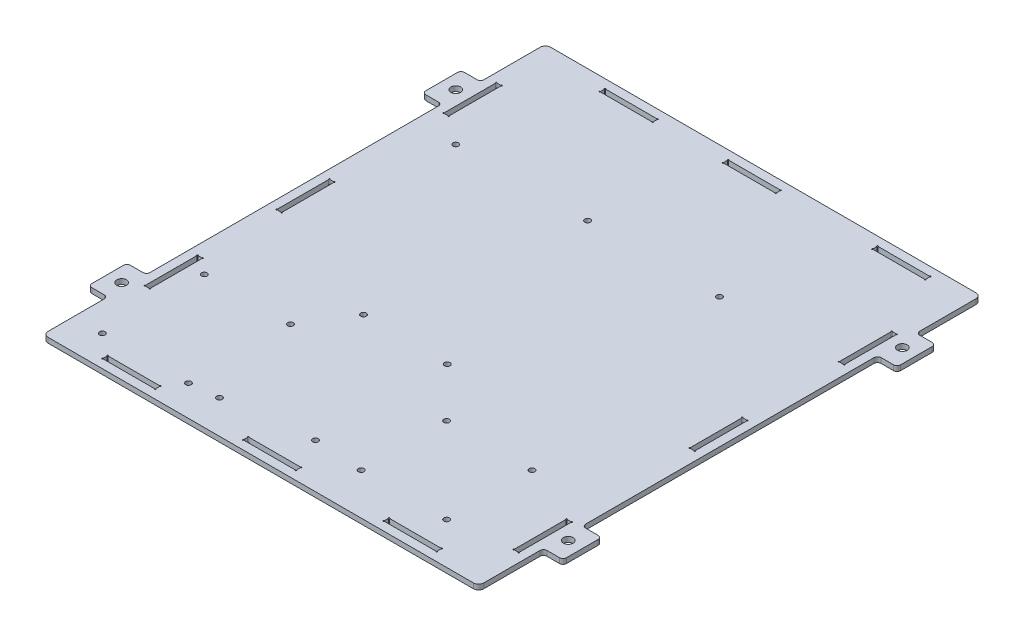
SolidWorks part; units mm, degrees
material "Acrylic (Medium-high impact)"
ref_plane "Front Plane" through (0, 0, 0) normal (0, 0, 1) x (1, 0, 0)
ref_plane "Top Plane" through (0, 0, 0) normal (0, 1, 0) x (1, 0, 0)
ref_plane "Right Plane" through (0, 0, 0) normal (1, 0, 0) x (0, 0, -1)
sketch "Sketch1" plane through (0, 0, 0) normal (0, 1, 0) x (1, 0, 0)
  line L0 (-120.9, -142.9) -> (120.9, -142.9)
  line L1 (123.9, -139.9) -> (123.9, -108)
  line L2 (125.9, -106) -> (133, -106)
  line L3 (135, -104) -> (135, -86)
  line L4 (133, -84) -> (125.9, -84)
  line L5 (123.9, -82) -> (123.9, 82)
  line L6 (125.9, 84) -> (133, 84)
  line L7 (135, 86) -> (135, 104)
  line L8 (133, 106) -> (125.9, 106)
  line L9 (123.9, 108) -> (123.9, 139.9)
  line L10 (120.9, 142.9) -> (-120.9, 142.9)
  line L11 (-123.9, 139.9) -> (-123.9, 108)
  line L12 (-125.9, 106) -> (-133, 106)
  line L13 (-135, 104) -> (-135, 86)
  line L14 (-133, 84) -> (-125.9, 84)
  line L15 (-123.9, 82) -> (-123.9, -82)
  line L16 (-125.9, -84) -> (-133, -84)
  line L17 (-135, -86) -> (-135, -104)
  line L18 (-133, -106) -> (-125.9, -106)
  line L19 (-123.9, -108) -> (-123.9, -139.9)
  line L20 (-94.6375, -137.9) -> (-65.3625, -137.9)
  line L21 (-65.0125, -137.55) -> (-65.0125, -135.35)
  line L22 (-65.3625, -135) -> (-94.6375, -135)
  line L23 (-94.9875, -135.35) -> (-94.9875, -137.55)
  line L24 (-14.6375, -137.9) -> (14.6375, -137.9)
  line L25 (14.9875, -137.55) -> (14.9875, -135.35)
  line L26 (14.6375, -135) -> (-14.6375, -135)
  line L27 (-14.9875, -135.35) -> (-14.9875, -137.55)
  line L28 (65.3625, -137.9) -> (94.6375, -137.9)
  line L29 (94.9875, -137.55) -> (94.9875, -135.35)
  line L30 (94.6375, -135) -> (65.3625, -135)
  line L31 (65.0125, -135.35) -> (65.0125, -137.55)
  line L32 (-84.6375, 135) -> (-55.3625, 135)
  line L33 (-55.0125, 135.35) -> (-55.0125, 137.55)
  line L34 (-55.3625, 137.9) -> (-84.6375, 137.9)
  line L35 (-84.9875, 137.55) -> (-84.9875, 135.35)
  line L36 (-14.6375, 135) -> (14.6375, 135)
  line L37 (14.9875, 135.35) -> (14.9875, 137.55)
  line L38 (14.6375, 137.9) -> (-14.6375, 137.9)
  line L39 (-14.9875, 137.55) -> (-14.9875, 135.35)
  line L40 (70.3625, 135) -> (99.6375, 135)
  line L41 (99.9875, 135.35) -> (99.9875, 137.55)
  line L42 (99.6375, 137.9) -> (70.3625, 137.9)
  line L43 (70.0125, 137.55) -> (70.0125, 135.35)
  line L44 (116.35, -114.9875) -> (118.55, -114.9875)
  line L45 (118.9, -114.6375) -> (118.9, -85.3625)
  line L46 (118.55, -85.0125) -> (116.35, -85.0125)
  line L47 (116, -85.3625) -> (116, -114.6375)
  line L48 (116.35, -14.9875) -> (118.55, -14.9875)
  line L49 (118.9, -14.6375) -> (118.9, 14.6375)
  line L50 (118.55, 14.9875) -> (116.35, 14.9875)
  line L51 (116, 14.6375) -> (116, -14.6375)
  line L52 (116.35, 70.0125) -> (118.55, 70.0125)
  line L53 (118.9, 70.3625) -> (118.9, 99.6375)
  line L54 (118.55, 99.9875) -> (116.35, 99.9875)
  line L55 (116, 99.6375) -> (116, 70.3625)
  line L56 (-118.55, -89.9875) -> (-116.35, -89.9875)
  line L57 (-116, -89.6375) -> (-116, -60.3625)
  line L58 (-116.35, -60.0125) -> (-118.55, -60.0125)
  line L59 (-118.9, -60.3625) -> (-118.9, -89.6375)
  line L60 (-118.55, -14.9875) -> (-116.35, -14.9875)
  line L61 (-116, -14.6375) -> (-116, 14.6375)
  line L62 (-116.35, 14.9875) -> (-118.55, 14.9875)
  line L63 (-118.9, 14.6375) -> (-118.9, -14.6375)
  line L64 (-118.55, 80.0125) -> (-116.35, 80.0125)
  line L65 (-116, 80.3625) -> (-116, 109.6375)
  line L66 (-116.35, 109.9875) -> (-118.55, 109.9875)
  line L67 (-118.9, 109.6375) -> (-118.9, 80.3625)
  arc A0 (-123.9, -139.9) -> (-120.9, -142.9) centre (-120.9, -139.9) ccw
  arc A1 (120.9, -142.9) -> (123.9, -139.9) centre (120.9, -139.9) ccw
  arc A2 (125.9, -106) -> (123.9, -108) centre (125.9, -108) ccw
  arc A3 (133, -106) -> (135, -104) centre (133, -104) ccw
  arc A4 (135, -86) -> (133, -84) centre (133, -86) ccw
  arc A5 (123.9, -82) -> (125.9, -84) centre (125.9, -82) ccw
  arc A6 (125.9, 84) -> (123.9, 82) centre (125.9, 82) ccw
  arc A7 (133, 84) -> (135, 86) centre (133, 86) ccw
  arc A8 (135, 104) -> (133, 106) centre (133, 104) ccw
  arc A9 (123.9, 108) -> (125.9, 106) centre (125.9, 108) ccw
  arc A10 (123.9, 139.9) -> (120.9, 142.9) centre (120.9, 139.9) ccw
  arc A11 (-120.9, 142.9) -> (-123.9, 139.9) centre (-120.9, 139.9) ccw
  arc A12 (-125.9, 106) -> (-123.9, 108) centre (-125.9, 108) ccw
  arc A13 (-133, 106) -> (-135, 104) centre (-133, 104) ccw
  arc A14 (-135, 86) -> (-133, 84) centre (-133, 86) ccw
  arc A15 (-123.9, 82) -> (-125.9, 84) centre (-125.9, 82) ccw
  arc A16 (-125.9, -84) -> (-123.9, -82) centre (-125.9, -82) ccw
  arc A17 (-133, -84) -> (-135, -86) centre (-133, -86) ccw
  arc A18 (-135, -104) -> (-133, -106) centre (-133, -104) ccw
  arc A19 (-123.9, -108) -> (-125.9, -106) centre (-125.9, -108) ccw
  circle A20 centre (-107.5, -125.5) radius 1.6
  circle A21 centre (-107.5, -67.5) radius 1.6
  circle A22 centre (-58.5, -125.5) radius 1.6
  circle A23 centre (-58.5, -67.5) radius 1.6
  circle A24 centre (5.8, -42.64) radius 1.6
  circle A25 centre (5.8, -117.57) radius 1.6
  circle A26 centre (-42.46, -123.92) radius 1.6
  circle A27 centre (-42.46, -42) radius 1.6
  circle A28 centre (82.1, -70.7) radius 1.6
  circle A29 centre (82.1, -119.3) radius 1.6
  circle A30 centre (33.5, -70.7) radius 1.6
  circle A31 centre (33.5, -119.3) radius 1.6
  circle A32 centre (-100, 68) radius 1.6
  circle A33 centre (-25, 68) radius 1.6
  circle A34 centre (50, 68) radius 1.6
  circle A35 centre (-127, -95) radius 2.75
  circle A36 centre (-127, 95) radius 2.75
  circle A37 centre (127, -95) radius 2.75
  circle A38 centre (127, 95) radius 2.75
  arc A39 (-65.3625, -137.9) -> (-65.0125, -137.55) centre (-65.0125, -137.9) ccw
  arc A40 (-65.0125, -135.35) -> (-65.3625, -135) centre (-65.0125, -135) ccw
  arc A41 (-94.6375, -135) -> (-94.9875, -135.35) centre (-94.9875, -135) ccw
  arc A42 (-94.9875, -137.55) -> (-94.6375, -137.9) centre (-94.9875, -137.9) ccw
  arc A43 (14.6375, -137.9) -> (14.9875, -137.55) centre (14.9875, -137.9) ccw
  arc A44 (14.9875, -135.35) -> (14.6375, -135) centre (14.9875, -135) ccw
  arc A45 (-14.6375, -135) -> (-14.9875, -135.35) centre (-14.9875, -135) ccw
  arc A46 (-14.9875, -137.55) -> (-14.6375, -137.9) centre (-14.9875, -137.9) ccw
  arc A47 (94.6375, -137.9) -> (94.9875, -137.55) centre (94.9875, -137.9) ccw
  arc A48 (94.9875, -135.35) -> (94.6375, -135) centre (94.9875, -135) ccw
  arc A49 (65.3625, -135) -> (65.0125, -135.35) centre (65.0125, -135) ccw
  arc A50 (65.0125, -137.55) -> (65.3625, -137.9) centre (65.0125, -137.9) ccw
  arc A51 (-55.3625, 135) -> (-55.0125, 135.35) centre (-55.0125, 135) ccw
  arc A52 (-55.0125, 137.55) -> (-55.3625, 137.9) centre (-55.0125, 137.9) ccw
  arc A53 (-84.6375, 137.9) -> (-84.9875, 137.55) centre (-84.9875, 137.9) ccw
  arc A54 (-84.9875, 135.35) -> (-84.6375, 135) centre (-84.9875, 135) ccw
  arc A55 (14.6375, 135) -> (14.9875, 135.35) centre (14.9875, 135) ccw
  arc A56 (14.9875, 137.55) -> (14.6375, 137.9) centre (14.9875, 137.9) ccw
  arc A57 (-14.6375, 137.9) -> (-14.9875, 137.55) centre (-14.9875, 137.9) ccw
  arc A58 (-14.9875, 135.35) -> (-14.6375, 135) centre (-14.9875, 135) ccw
  arc A59 (99.6375, 135) -> (99.9875, 135.35) centre (99.9875, 135) ccw
  arc A60 (99.9875, 137.55) -> (99.6375, 137.9) centre (99.9875, 137.9) ccw
  arc A61 (70.3625, 137.9) -> (70.0125, 137.55) centre (70.0125, 137.9) ccw
  arc A62 (70.0125, 135.35) -> (70.3625, 135) centre (70.0125, 135) ccw
  arc A63 (118.55, -114.9875) -> (118.9, -114.6375) centre (118.9, -114.9875) ccw
  arc A64 (118.9, -85.3625) -> (118.55, -85.0125) centre (118.9, -85.0125) ccw
  arc A65 (116.35, -85.0125) -> (116, -85.3625) centre (116, -85.0125) ccw
  arc A66 (116, -114.6375) -> (116.35, -114.9875) centre (116, -114.9875) ccw
  arc A67 (118.55, -14.9875) -> (118.9, -14.6375) centre (118.9, -14.9875) ccw
  arc A68 (118.9, 14.6375) -> (118.55, 14.9875) centre (118.9, 14.9875) ccw
  arc A69 (116.35, 14.9875) -> (116, 14.6375) centre (116, 14.9875) ccw
  arc A70 (116, -14.6375) -> (116.35, -14.9875) centre (116, -14.9875) ccw
  arc A71 (118.55, 70.0125) -> (118.9, 70.3625) centre (118.9, 70.0125) ccw
  arc A72 (118.9, 99.6375) -> (118.55, 99.9875) centre (118.9, 99.9875) ccw
  arc A73 (116.35, 99.9875) -> (116, 99.6375) centre (116, 99.9875) ccw
  arc A74 (116, 70.3625) -> (116.35, 70.0125) centre (116, 70.0125) ccw
  arc A75 (-116.35, -89.9875) -> (-116, -89.6375) centre (-116, -89.9875) ccw
  arc A76 (-116, -60.3625) -> (-116.35, -60.0125) centre (-116, -60.0125) ccw
  arc A77 (-118.55, -60.0125) -> (-118.9, -60.3625) centre (-118.9, -60.0125) ccw
  arc A78 (-118.9, -89.6375) -> (-118.55, -89.9875) centre (-118.9, -89.9875) ccw
  arc A79 (-116.35, -14.9875) -> (-116, -14.6375) centre (-116, -14.9875) ccw
  arc A80 (-116, 14.6375) -> (-116.35, 14.9875) centre (-116, 14.9875) ccw
  arc A81 (-118.55, 14.9875) -> (-118.9, 14.6375) centre (-118.9, 14.9875) ccw
  arc A82 (-118.9, -14.6375) -> (-118.55, -14.9875) centre (-118.9, -14.9875) ccw
  arc A83 (-116.35, 80.0125) -> (-116, 80.3625) centre (-116, 80.0125) ccw
  arc A84 (-116, 109.6375) -> (-116.35, 109.9875) centre (-116, 109.9875) ccw
  arc A85 (-118.55, 109.9875) -> (-118.9, 109.6375) centre (-118.9, 109.9875) ccw
  arc A86 (-118.9, 80.3625) -> (-118.55, 80.0125) centre (-118.9, 80.0125) ccw
extrude "Boss-Extrude1" add sketch "Sketch1" along normal blind 2.9
